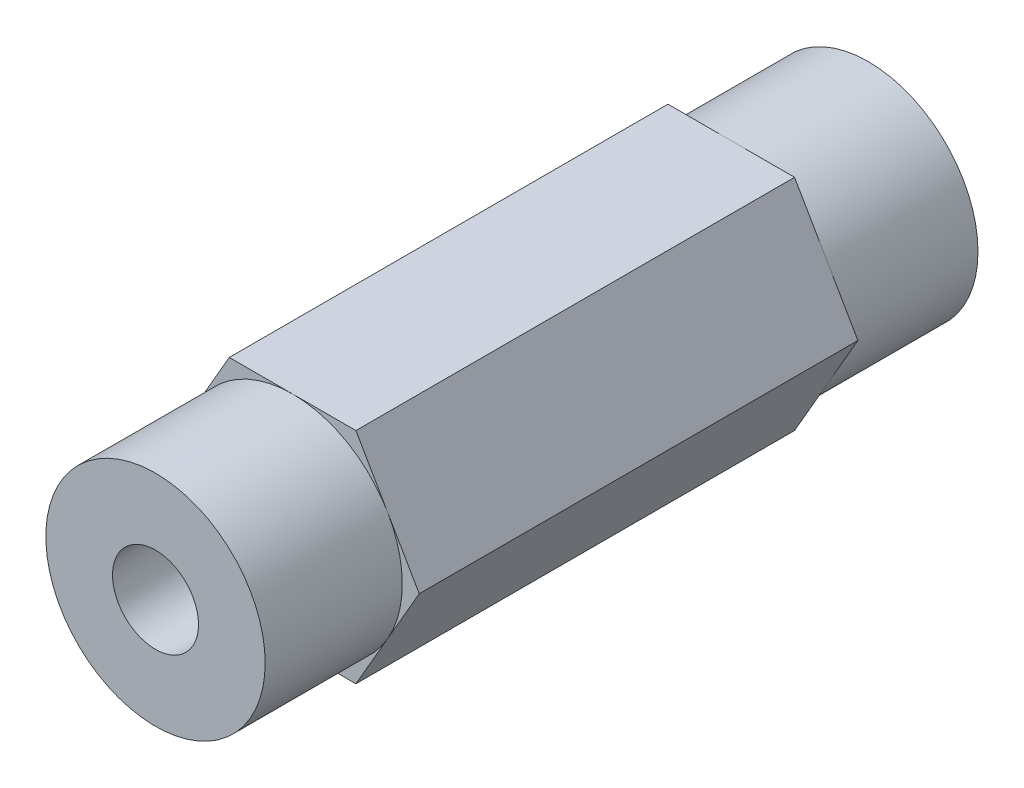
SolidWorks part; units mm, degrees
material "6061-T6 (SS)"
ref_plane "Front Plane" through (0, 0, 0) normal (0, 0, 1) x (1, 0, 0)
ref_plane "Top Plane" through (0, 0, 0) normal (0, 1, 0) x (1, 0, 0)
ref_plane "Right Plane" through (0, 0, 0) normal (1, 0, 0) x (0, 0, -1)
sketch "Sketch1" plane through (0, 0, 0) normal (0, 0, 1) x (1, 0, 0)
  line L1 (3.6662, 6.35) -> (-3.6662, 6.35)
  line L2 (-3.6662, 6.35) -> (-7.3323, 0)
  line L3 (-7.3323, 0) -> (-3.6662, -6.35)
  line L4 (-3.6662, -6.35) -> (3.6662, -6.35)
  line L5 (3.6662, -6.35) -> (7.3323, 0)
  line L6 (7.3323, 0) -> (3.6662, 6.35)
  circle A0 centre (0, 0) radius 6.35 construction
  circle A1 centre (0, 0) radius 2.4892
  point P1 (0, 6.35)
  dimension "D1" = 12.7
  dimension "D2" = 4.9784
extrude "Boss-Extrude1" add sketch "Sketch1" along normal mid plane 41.275
sketch "Sketch2" plane through (0, 0, 20.6375) normal (0, 0, 1) x (1, 0, 0)
  circle A0 centre (0, 0) radius 6.35
  dimension "D1" = 12.7
extrude "Cut-Extrude4" cut sketch "Sketch2" against normal blind 7.9375 flip side to cut contours A0
mirror "Mirror1" about plane through (0, 0, 0) normal (0, 0, 1) of "Cut-Extrude4"
